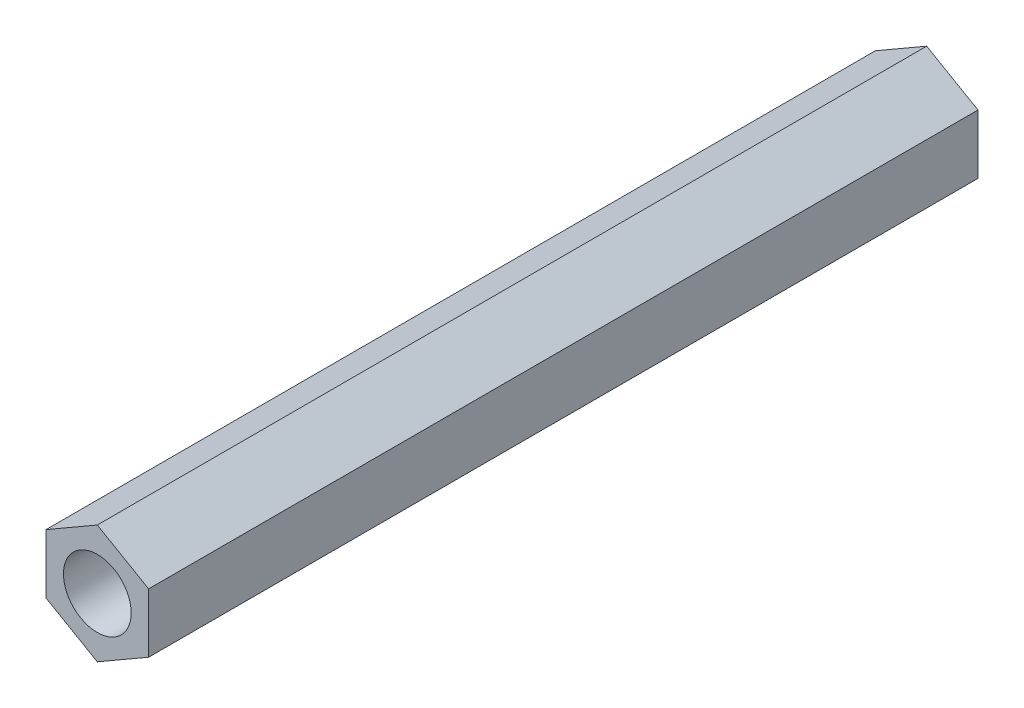
SolidWorks part; units mm, degrees
ref_plane "Plan de face" through (0, 0, 0) normal (0, 0, 1) x (1, 0, 0)
ref_plane "Plan de dessus" through (0, 0, 0) normal (0, 1, 0) x (1, 0, 0)
ref_plane "Plan de droite" through (0, 0, 0) normal (1, 0, 0) x (0, 0, -1)
sketch "Esquisse1" plane through (0, 0, 0) normal (0, 0, 1) x (1, 0, 0)
  line L1 (3.0311, -1.75) -> (3.0311, 1.75)
  line L2 (3.0311, 1.75) -> (0, 3.5)
  line L3 (0, 3.5) -> (-3.0311, 1.75)
  line L4 (-3.0311, 1.75) -> (-3.0311, -1.75)
  line L5 (-3.0311, -1.75) -> (0, -3.5)
  line L6 (0, -3.5) -> (3.0311, -1.75)
  circle A0 centre (0, 0) radius 3.0311 construction
  circle A1 centre (0, 0) radius 2
  dimension "D2" = 4
  dimension "D1" = 7
extrude "Boss.-Extru.1" add sketch "Esquisse1" along normal blind 49
